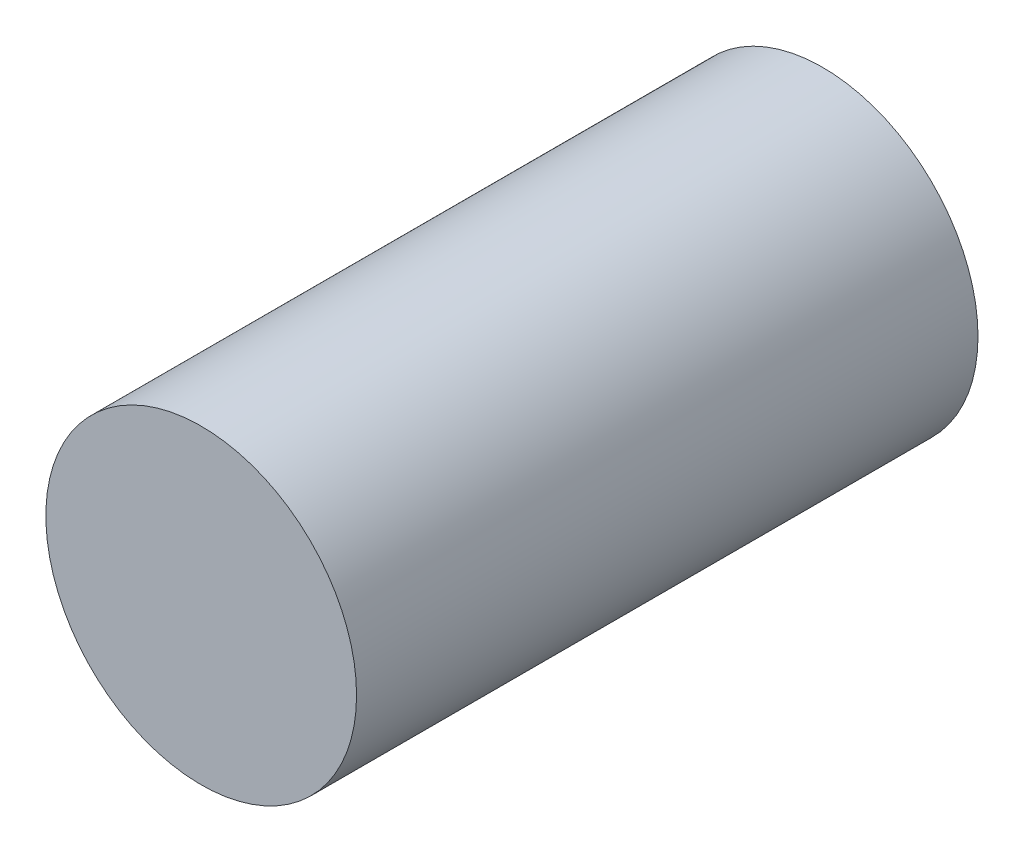
SolidWorks part; units mm, degrees
ref_plane "Front Plane" through (0, 0, 0) normal (0, 0, 1) x (1, 0, 0)
ref_plane "Top Plane" through (0, 0, 0) normal (0, 1, 0) x (1, 0, 0)
ref_plane "Right Plane" through (0, 0, 0) normal (1, 0, 0) x (0, 0, -1)
sketch "Sketch2" plane through (0, 0, 0) normal (0, 0, 1) x (1, 0, 0)
  circle A0 centre (0, 0) radius 50
  dimension "D1" = 100
extrude "Boss-Extrude1" add sketch "Sketch2" along normal blind 200
